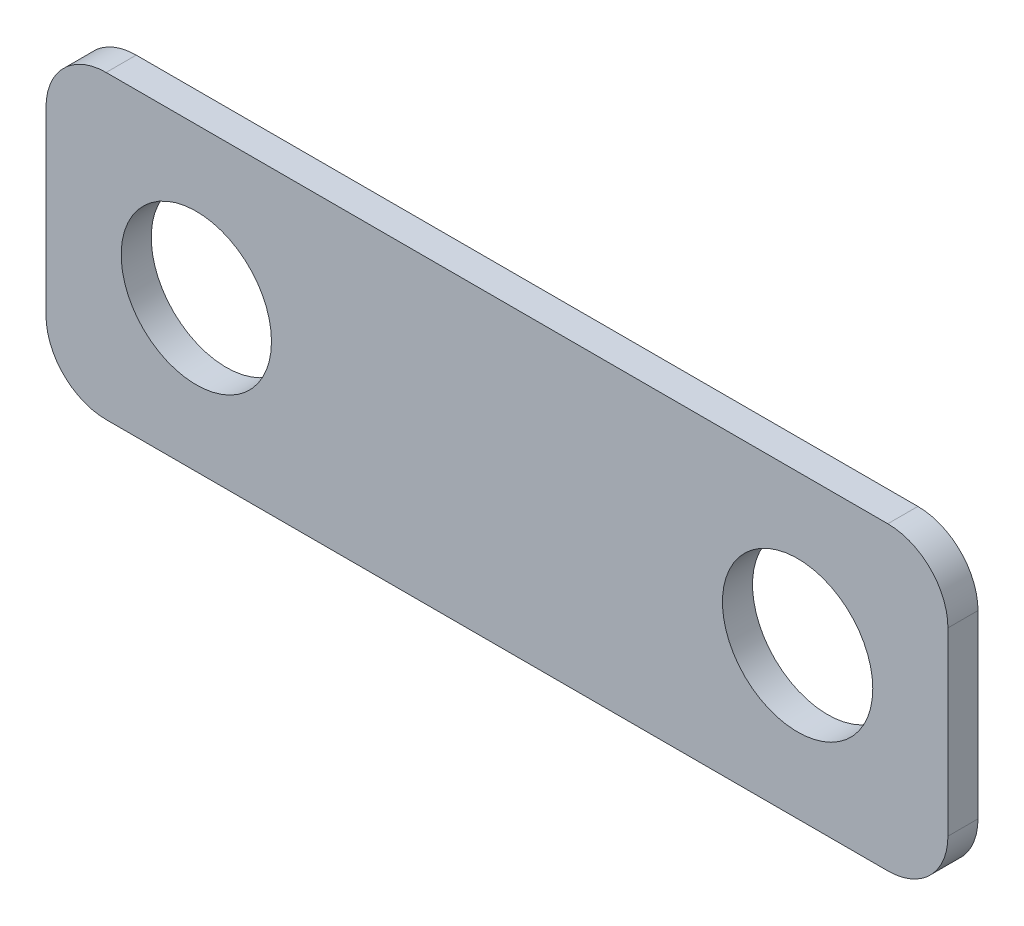
SolidWorks part; units mm, degrees
ref_plane "Front Plane" through (0, 0, 0) normal (0, 0, 1) x (1, 0, 0)
ref_plane "Top Plane" through (0, 0, 0) normal (0, 1, 0) x (1, 0, 0)
ref_plane "Right Plane" through (0, 0, 0) normal (1, 0, 0) x (0, 0, -1)
sketch "Sketch1" plane through (0, 0, 0) normal (0, 0, 1) x (1, 0, 0)
  line L1 (-13, -5) -> (13, -5)
  line L2 (-15, -3) -> (-15, 3)
  line L3 (-13, 5) -> (13, 5)
  line L4 (15, -3) -> (15, 3)
  line L5 (-15, -5) -> (15, 5) construction
  line L6 (-15, 5) -> (15, -5) construction
  circle A0 centre (-10, 0) radius 2.5
  circle A1 centre (10, 0) radius 2.5
  arc A2 (13, 5) -> (15, 3) centre (13, 3) cw
  arc A3 (13, -5) -> (15, -3) centre (13, -3) ccw
  arc A4 (-13, -5) -> (-15, -3) centre (-13, -3) cw
  arc A5 (-15, 3) -> (-13, 5) centre (-13, 3) cw
  point P0 (0, 0)
  dimension "D3" = 5
  dimension "D5" = 5
  dimension "D6" = 2
  dimension "D1" = 10
  dimension "D2" = 30
  dimension "D4" = 5
extrude "Boss-Extrude1" add sketch "Sketch1" along normal blind 1
